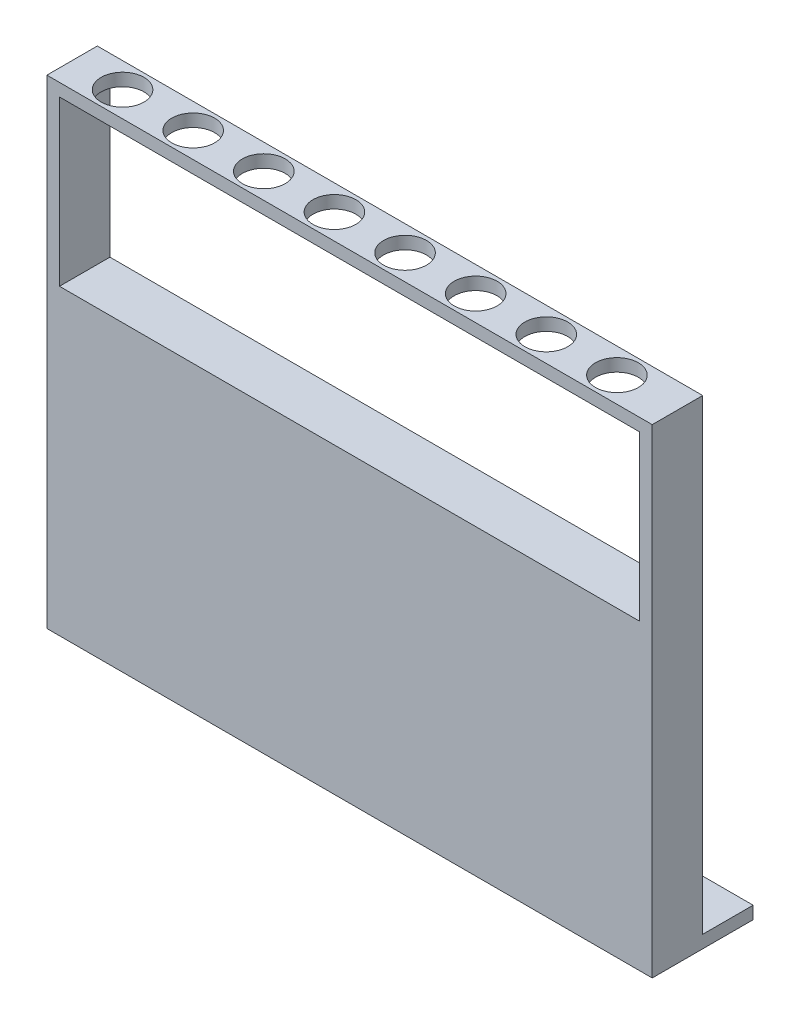
SolidWorks part; units mm, degrees
ref_plane "Front Plane" through (0, 0, 0) normal (0, 0, 1) x (1, 0, 0)
ref_plane "Top Plane" through (0, 0, 0) normal (0, 1, 0) x (1, 0, 0)
ref_plane "Right Plane" through (0, 0, 0) normal (1, 0, 0) x (0, 0, -1)
sketch "Sketch1" plane through (0, 0, 0) normal (0, 1, 0) x (1, 0, 0)
  line L1 (-76.2, -6.35) -> (76.2, -6.35)
  line L2 (-76.2, -6.35) -> (-76.2, 6.35)
  line L3 (-76.2, 6.35) -> (76.2, 6.35)
  line L4 (76.2, -6.35) -> (76.2, 6.35)
  line L5 (-76.2, -6.35) -> (76.2, 6.35) construction
  line L6 (-76.2, 6.35) -> (76.2, -6.35) construction
  point P0 (0, 0)
  dimension "D1" = 12.7
  dimension "D2" = 152.4
extrude "Boss-Extrude1" add sketch "Sketch1" along normal blind 76.2
sketch "Sketch2" plane through (0, 0, 0) normal (0, 1, 0) x (1, 0, 0)
  line L0 (-76.2, 6.35) -> (-76.2, -6.35) construction
  line L1 (-76.2, 12.7) -> (-76.2, 6.35)
  line L2 (-76.2, 6.35) -> (76.2, 6.35)
  line L3 (76.2, 19.05) -> (-76.2, 19.05)
  line L4 (-76.2, 12.7) -> (-76.2, 19.05)
  line L5 (0, 0) -> (-76.2, 19.05) construction
  line L6 (76.2, 19.05) -> (0, 0) construction
  line L7 (76.2, 6.35) -> (-76.2, 6.35) construction
  line L8 (-23.5905, 19.05) -> (-23.5905, 6.35) construction
  line L9 (-23.5905, 12.7) -> (-76.2, 12.7) construction
  line L10 (76.2, 6.35) -> (76.2, 19.05)
  circle A0 centre (-69.85, 12.7) radius 3.175
  circle A1 centre (-44.45, 12.7) radius 3.175
  circle A2 centre (-19.05, 12.7) radius 3.175
  circle A3 centre (6.35, 12.7) radius 3.175
  circle A4 centre (31.75, 12.7) radius 3.175
  circle A5 centre (57.15, 12.7) radius 3.175
  point P0 (0, 0)
  dimension "D2" = 6.35
  dimension "D1" = 12.7
  dimension "D3" = 6
  dimension "D4" = 6.35
extrude "Boss-Extrude4" add sketch "Sketch2" along normal blind 3.175
sketch "Sketch3" plane through (0, 0, 6.35) normal (0, 0, 1) x (1, 0, 0)
  line L0 (-76.2, 76.2) -> (-76.2, 120.65)
  line L1 (-76.2, 120.65) -> (76.2, 120.65)
  line L2 (76.2, 120.65) -> (76.2, 76.2)
  line L3 (76.2, 76.2) -> (76.2, 0) construction
  line L4 (-76.2, 76.2) -> (-76.2, 0) construction
  line L5 (76.2, 76.2) -> (73.025, 76.2)
  line L6 (-76.2, 76.2) -> (76.2, 76.2) construction
  line L7 (73.025, 76.2) -> (73.025, 117.475)
  line L8 (73.025, 117.475) -> (-73.025, 117.475)
  line L9 (-73.025, 117.475) -> (-73.025, 76.2)
  line L10 (-73.025, 76.2) -> (-76.2, 76.2)
  line L11 (-73.025, 117.475) -> (-73.025, 120.65) construction
  dimension "D1" = 3.175
  dimension "D2" = 44.45
extrude "Boss-Extrude5" add sketch "Sketch3" against normal up to surface (12.7 mm away) up to face at (0, 39.6875, -6.35)
sketch "Sketch4" plane through (0, 120.65, 0) normal (0, 1, 0) x (1, 0, 0)
  line L0 (-76.2, 6.35) -> (-76.2, -6.35) construction
  circle A0 centre (-63.5, 0) radius 5.3975
  circle A1 centre (-45.72, 0) radius 5.3975
  circle A2 centre (-27.94, 0) radius 5.3975
  circle A3 centre (-10.16, 0) radius 5.3975
  circle A4 centre (7.62, 0) radius 5.3975
  circle A5 centre (25.4, 0) radius 5.3975
  circle A6 centre (43.18, 0) radius 5.3975
  circle A7 centre (60.96, 0) radius 5.3975
  dimension "D1" = 10.795
  dimension "D2" = 12.7
  dimension "D3" = 8
extrude "Cut-Extrude1" cut sketch "Sketch4" against normal up to next
